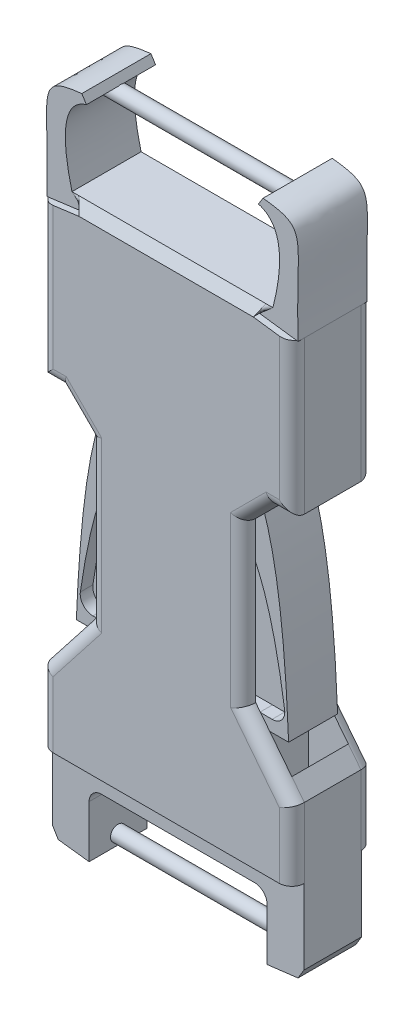
SolidWorks part; units mm, degrees
ref_plane "Front Plane" through (0, 0, 0) normal (0, 0, 1) x (1, 0, 0)
ref_plane "Top Plane" through (0, 0, 0) normal (0, 1, 0) x (1, 0, 0)
ref_plane "Right Plane" through (0, 0, 0) normal (1, 0, 0) x (0, 0, -1)
sketch "Sketch1" plane through (0, 0, 0) normal (0, 0, 1) x (1, 0, 0)
  line L0 (-10, 0) -> (10, 0)
  line L1 (10, 0) -> (10, 5.5785)
  line L2 (10, 5.5785) -> (6.1284, 10.5196)
  line L3 (6.1284, 10.5196) -> (6.1284, 23.2092)
  line L4 (10, 25.4423) -> (8.3615, 25.4423)
  line L5 (10, 25.4423) -> (10, 37.5927)
  line L6 (6.9273, 38) -> (-6.9273, 38)
  line L7 (0, 0) -> (0, 5.5785) construction
  line L8 (6.9273, 38) -> (10, 37.5927)
  line L9 (8.3615, 25.4423) -> (6.1284, 23.2092)
  line L10 (6.1284, 23.2092) -> (11.5216, 23.2092) construction
  line L11 (-6.1284, 23.2092) -> (-11.5216, 23.2092) construction
  line L12 (-8.3615, 25.4423) -> (-6.1284, 23.2092)
  line L13 (-6.9273, 38) -> (-10, 37.5927)
  line L14 (-10, 25.4423) -> (-10, 37.5927)
  line L15 (-10, 25.4423) -> (-8.3615, 25.4423)
  line L16 (-6.1284, 10.5196) -> (-6.1284, 23.2092)
  line L17 (-10, 5.5785) -> (-6.1284, 10.5196)
  line L18 (-10, 0) -> (-10, 5.5785)
  point P8 (0, 38)
  point P24 (0, 38)
  dimension "D1" = 10
  dimension "D2" = 38
  dimension "D3" = 45
  dimension "D4" = 20
extrude "Boss-Extrude1" add sketch "Sketch1" along normal mid plane 6.5
fillet "Fillet1" radius 1 24 edges at (-10, 2.7892, -3.25) (10, 31.5175, 3.25) (9.1807, 25.4423, 3.25) (7.2449, 24.3257, 3.25) (6.1284, 16.8644, 3.25) (10, 2.7892, 3.25) (8.0642, 8.049, 3.25) (10, 31.5175, -3.25) (9.1807, 25.4423, -3.25) (7.2449, 24.3257, -3.25) (6.1284, 16.8644, -3.25) (8.0642, 8.049, -3.25) (10, 2.7892, -3.25) (-10, 31.5175, 3.25) (-9.1807, 25.4423, 3.25) (-7.2449, 24.3257, 3.25) (-6.1284, 16.8644, 3.25) (-8.0642, 8.049, 3.25) (-10, 2.7892, 3.25) (-9.1807, 25.4423, -3.25) (-10, 31.5175, -3.25) (-7.2449, 24.3257, -3.25) (-6.1284, 16.8644, -3.25) (-8.0642, 8.049, -3.25)
sketch "Sketch2" plane through (0, 0, 0) normal (0, -1, 0) x (1, 0, 0)
  line L8 (9, -2.25) -> (9, 2.25)
  line L9 (9, 2.25) -> (-9, 2.25)
  line L10 (-9, 2.25) -> (-9, -2.25)
  line L11 (-9, -2.25) -> (9, -2.25)
  line L12 (9, -2.25) -> (9, 2.25)
  line L13 (9, 2.25) -> (-9, 2.25)
  line L14 (-9, 2.25) -> (-9, -2.25)
  line L15 (-9, -2.25) -> (9, -2.25)
  dimension "D1" = 1
extrude "Cut-Extrude1" cut sketch "Sketch2" against normal blind 36.5
sketch "Sketch3" plane through (0, 0, 3.25) normal (0, 0, 1) x (1, 0, 0)
  line L0 (9.5, 37.659) -> (10, 37.5927)
  line L1 (10, 37.5927) -> (9, 37.7253) construction
  line L2 (7.2125, 46.0747) -> (6.8438, 45.4922)
  line L3 (0, 38) -> (0, 43.3866) construction
  line L4 (6.9273, 38) -> (-6.9273, 38) construction
  line L5 (7.9949, 38.9215) -> (-7.9949, 38.9215)
  line L6 (-7.2125, 46.0747) -> (-6.8438, 45.4922)
  line L7 (-9.5, 37.659) -> (-10, 37.5927)
  line L8 (-9.5, 37.659) -> (9.5, 37.659)
  line L9 (10, 25.4423) -> (10, 37.5927) construction
  spline S0 degree 3 poles (10, 37.5927) (9.7468, 44.8239) (11.0585, 45.6532) (7.2125, 46.0747) knots 0 0 0 0 1 1 1 1
  spline S1 degree 2 poles (6.8438, 45.4922) (9.473, 44.7164) (7.9949, 38.9215) knots 0 0 0 1 1 1
  spline S2 degree 2 poles (-6.8438, 45.4922) (-9.473, 44.7164) (-7.9949, 38.9215) knots 0 0 0 1 1 1
  spline S3 degree 3 poles (-10, 37.5927) (-9.7468, 44.8239) (-11.0585, 45.6532) (-7.2125, 46.0747) knots 0 0 0 0 1 1 1 1
  point P17 (0, 38.9215)
extrude "Boss-Extrude2" add sketch "Sketch3" against normal blind 5.5 from offset 0.5 offset against normal yes
curve "CompCurve1"
surface "Surface-Loft1"
mirror "Mirror1" about plane through (0, 0, 0) normal (0, 0, 1) of bodies 104
sketch "Sketch4" plane through (0, 0, 0) normal (1, 0, 0) x (0, 0, -1)
  line L0 (0, 46.0747) -> (0, 44.9113) construction
  line L1 (2.75, 46.0747) -> (-2.75, 46.0747) construction
  circle A0 centre (0, 44.9113) radius 0.6
extrude "Boss-Extrude3" add sketch "Sketch4" along normal blind 8 and the other way blind 8
sketch "Sketch5" plane through (0, 0, 0) normal (0, 0, 1) x (1, 0, 0)
  line L0 (-1.4268, 29.8544) -> (-1.4268, 28.7433)
  line L2 (-8.446, 8.7993) -> (-6.1451, 8.7993)
  line L3 (-6.1451, 8.7993) -> (-6.1451, 0)
  line L4 (-9, 0) -> (9, 0) construction
  line L5 (-6.1451, 0) -> (6.1451, 0)
  line L6 (-3.1148, 10.8797) -> (-3.1148, 3.9073)
  line L7 (-3.1148, 3.9073) -> (3.1148, 3.9073)
  line L8 (0, 0) -> (0, 6.947) construction
  line L9 (3.1148, 10.8797) -> (3.1148, 3.9073)
  line L10 (6.1451, 8.7993) -> (6.1451, 0)
  line L11 (8.446, 8.7993) -> (6.1451, 8.7993)
  line L12 (1.4268, 29.8544) -> (1.4268, 28.7433)
  spline S0 degree 3 poles (-1.4268, 29.8544) (-6.1718, 27.9903) (-7.8654, 22.4498) (-8.446, 8.7993) knots 0 0 0 0 1 1 1 1
  spline S1 degree 2 poles (-1.4268, 28.7433) (-2.9519, 25.9471) (-3.1148, 10.8797) knots 0 0 0 1 1 1
  spline S2 degree 2 poles (1.4268, 28.7433) (2.9519, 25.9471) (3.1148, 10.8797) knots 0 0 0 1 1 1
  spline S3 degree 3 poles (1.4268, 29.8544) (6.1718, 27.9903) (7.8654, 22.4498) (8.446, 8.7993) knots 0 0 0 0 1 1 1 1
  point P18 (0, 3.9073)
extrude "Boss-Extrude4" add sketch "Sketch5" along normal mid plane 3.9 separate body
sketch "Sketch6" plane through (0, 0, 3.25) normal (0, 0, 1) x (1, 0, 0)
  line L0 (0, 0) -> (0, -5.483) construction
  line L1 (10, 0) -> (-10, 0)
  line L2 (-10, 0) -> (-10, 5.5785) construction
  line L4 (-10, 0) -> (-10, -5.9635)
  line L5 (-10, -5.9635) -> (-9.5421, -6.7267)
  line L6 (-9.5421, -6.7267) -> (-7.0818, -7.0269)
  line L7 (-7.0818, -7.0269) -> (-7.0818, -2.8814)
  line L8 (-6.0818, -1.8814) -> (6.0818, -1.8814)
  line L9 (7.0818, -7.0269) -> (7.0818, -2.8814)
  line L10 (9.5421, -6.7267) -> (7.0818, -7.0269)
  line L11 (10, -5.9635) -> (9.5421, -6.7267)
  line L12 (10, 0) -> (10, -5.9635)
  arc A0 (7.0818, -2.8814) -> (6.0818, -1.8814) centre (6.0818, -2.8814) ccw
  arc A1 (-7.0818, -2.8814) -> (-6.0818, -1.8814) centre (-6.0818, -2.8814) cw
  point P15 (0, -1.8814)
  point P20 (7.0818, -1.8814)
  point P23 (-7.0818, -1.8814)
  dimension "D1" = 1
extrude "Boss-Extrude5" add sketch "Sketch6" against normal blind 4.6 from offset 0.95 offset against normal yes
sketch "Sketch7" plane through (0, 0, 0) normal (1, 0, 0) x (0, 0, -1)
  line L0 (0, -6.7267) -> (0, -6.1916) construction
  line L1 (2.3, -6.7267) -> (-2.3, -6.7267) construction
  circle A0 centre (0, -6.1916) radius 0.6
extrude "Boss-Extrude6" add sketch "Sketch7" along normal blind 8 and the other way blind 8
sketch "Sketch8" plane through (0, 0, -1.95) normal (0, 0, -1) x (-1, 0, 0)
  line L0 (4.5737, 20.3095) -> (4.5737, 9.7289)
  line L1 (4.5737, 9.7289) -> (6.1608, 9.7289)
  line L2 (0, 0) -> (0, 4.3861) construction
  line L3 (9, 0) -> (-9, 0) construction
  line L4 (-5.1237, 21.1672) -> (-4.5737, 20.3095)
  line L5 (-6.1608, 9.7289) -> (-7.1302, 9.7197)
  line L6 (-4.5737, 9.7289) -> (-6.1608, 9.7289)
  line L7 (-4.5737, 20.3095) -> (-4.5737, 9.7289)
  line L10 (6.1608, 9.7289) -> (7.1302, 9.7197)
  line L11 (5.1237, 21.1672) -> (4.5737, 20.3095)
  arc A0 (7.1302, 9.7197) -> (8.1293, 10.8635) centre (7.1397, 10.7197) ccw
  arc A1 (-8.1293, 10.8635) -> (-7.1302, 9.7197) centre (-7.1397, 10.7197) ccw
  spline S0 degree 3 poles (-8.1293, 10.8635) (-8.0982, 11.0776) (-8.0013, 11.7259) (-7.7669, 13.1574) (-7.3967, 15.0473) (-6.8985, 17.0296) (-6.3435, 18.7346) (-5.7514, 20.116) (-5.3303, 20.854) (-5.1237, 21.1672) knots 0.053188 0.053188 0.053188 0.053188 0.079277 0.132605 0.23926 0.345915 0.452571 0.559226 0.655925 0.655925 0.655925 0.655925
  spline S3 degree 3 poles (8.1293, 10.8635) (8.0982, 11.0776) (8.0013, 11.7259) (7.7669, 13.1574) (7.3967, 15.0473) (6.8985, 17.0296) (6.3435, 18.7346) (5.7514, 20.116) (5.3303, 20.854) (5.1237, 21.1672) knots 0.053188 0.053188 0.053188 0.053188 0.079277 0.132605 0.23926 0.345915 0.452571 0.559226 0.655925 0.655925 0.655925 0.655925
  spline M25 degree 2 poles (1.4268, 28.7433) (2.9519, 25.9471) (3.1148, 10.8797) knots 0 0 0 1 1 1
  spline M29 degree 2 poles (-3.1148, 10.8797) (-2.9519, 25.9471) (-1.4268, 28.7433) knots 0 0 0 1 1 1
  dimension "D1" = 1
extrude "Cut-Extrude2" cut sketch "Sketch8" against normal blind 1 contours S0 A1 L5 L6 L7 L4 M29 | A0 S3 L11 L0 L1 L10 M25
mirror "Mirror2" about plane through (0, 0, 0) normal (0, 0, 1) of "Cut-Extrude2"
